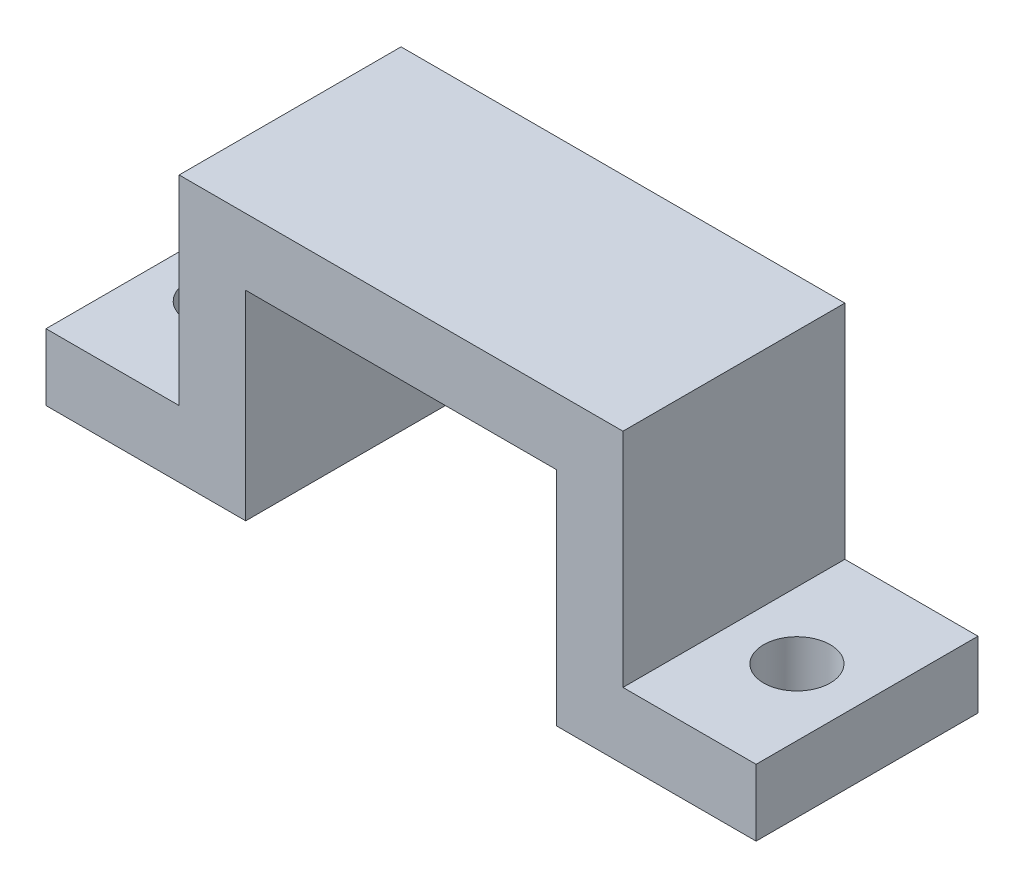
SolidWorks part; units mm, degrees
ref_plane "Front Plane" through (0, 0, 0) normal (0, 0, 1) x (1, 0, 0)
ref_plane "Top Plane" through (0, 0, 0) normal (0, 1, 0) x (1, 0, 0)
ref_plane "Right Plane" through (0, 0, 0) normal (1, 0, 0) x (0, 0, -1)
sketch "Sketch1" plane through (0, 0, 0) normal (0, 1, 0) x (1, 0, 0)
  line L1 (0, 0) -> (9, 0)
  line L2 (0, 0) -> (0, 10)
  line L3 (0, 10) -> (9, 10)
  line L4 (9, 0) -> (9, 10)
  dimension "D1" = 9
  dimension "D2" = 10
extrude "Boss-Extrude1" add sketch "Sketch1" along normal blind 3
sketch "Sketch2" plane through (0, 3, 0) normal (0, 1, 0) x (1, 0, 0)
  line L0 (0, 0) -> (9, 0) construction
  line L1 (9, 10) -> (6, 10)
  line L2 (9, 10) -> (9, 0)
  line L3 (9, 0) -> (6, 0)
  line L4 (6, 10) -> (6, 0)
  dimension "D1" = 3
extrude "Boss-Extrude2" add sketch "Sketch2" along normal blind 9
sketch "Sketch3" plane through (9, 0, 0) normal (1, 0, 0) x (0, 0, -1)
  line L0 (10, 12) -> (10, 0) construction
  line L1 (0, 12) -> (10, 12)
  line L2 (0, 12) -> (0, 9)
  line L3 (0, 9) -> (10, 9)
  line L4 (10, 12) -> (10, 9)
  dimension "D1" = 3
extrude "Boss-Extrude3" add sketch "Sketch3" along normal blind 17
sketch "Sketch4" plane through (0, 9, 0) normal (0, -1, 0) x (1, 0, 0)
  line L0 (26, -10) -> (9, -10) construction
  line L1 (26, 0) -> (23, 0)
  line L2 (26, 0) -> (26, -10)
  line L3 (26, -10) -> (23, -10)
  line L4 (23, 0) -> (23, -10)
  dimension "D1" = 3
extrude "Boss-Extrude4" add sketch "Sketch4" along normal blind 10
sketch "Sketch5" plane through (26, 0, 0) normal (1, 0, 0) x (0, 0, -1)
  line L0 (10, -1) -> (10, 12) construction
  line L1 (0, -1) -> (10, -1)
  line L2 (0, -1) -> (0, 2)
  line L3 (0, 2) -> (10, 2)
  line L4 (10, -1) -> (10, 2)
  dimension "D1" = 3
extrude "Boss-Extrude5" add sketch "Sketch5" along normal blind 6
sketch "Sketch6" plane through (0, 3, 0) normal (0, 1, 0) x (1, 0, 0)
  line L0 (2.8516, 10) -> (2.8516, 0)
  line L1 (6, 10) -> (0, 10) construction
  line L2 (0, 0) -> (6, 0) construction
  line L3 (0, 5) -> (6, 5)
  line L4 (0, 10) -> (0, 0) construction
  line L5 (6, 10) -> (6, 0) construction
  line L6 (29, 10) -> (29, 0)
  line L7 (32, 10) -> (26, 10) construction
  line L8 (32, 0) -> (26, 0) construction
  line L9 (32, 5) -> (26, 5)
  line L10 (32, 10) -> (32, 0) construction
  line L11 (26, 10) -> (26, 0) construction
  circle A0 centre (29, 4.8401) radius 1.5
  circle A1 centre (2.8516, 5) radius 1.5
  dimension "D1" = 3
  dimension "D2" = 3
extrude "Cut-Extrude1" cut sketch "Sketch6" against normal blind 6 contours L0 A1 L3 | L3 A1 L0 | L0 A1 L3 | L3 A1 L0 | L6 A0 L9 | L9 A0 L6 | L6 A0 L9 | L9 A0 L6
